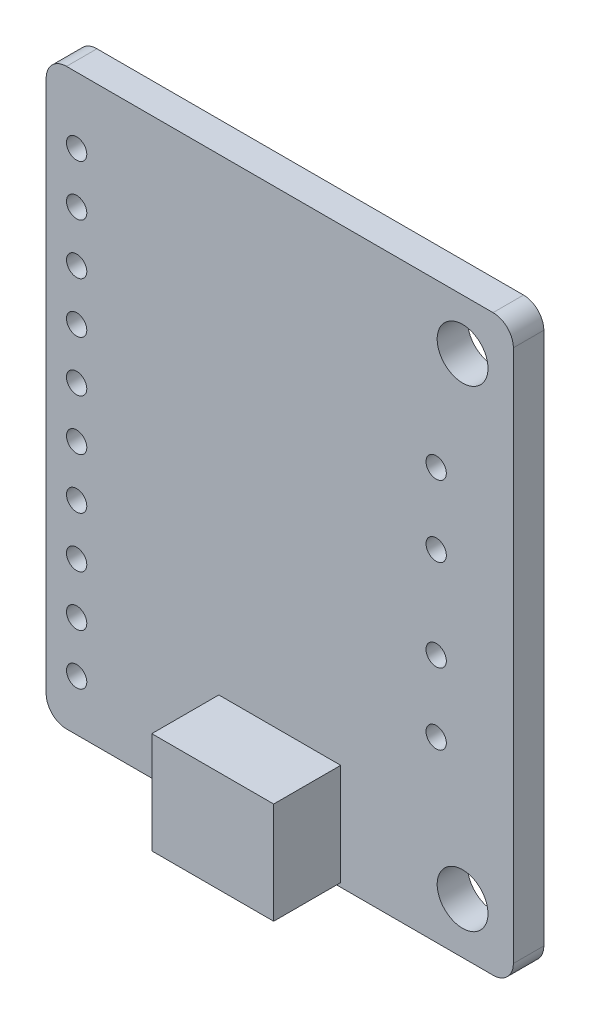
SolidWorks part; units mm, degrees
ref_plane "Front Plane" through (0, 0, 0) normal (0, 0, 1) x (1, 0, 0)
ref_plane "Top Plane" through (0, 0, 0) normal (0, 1, 0) x (1, 0, 0)
ref_plane "Right Plane" through (0, 0, 0) normal (1, 0, 0) x (0, 0, -1)
sketch "Sketch1" plane through (0, 0, 0) normal (0, 0, 1) x (1, 0, 0)
  line L1 (-10.5, -14.125) -> (10.5, -14.125)
  line L2 (-11.5, -13.125) -> (-11.5, 13.125)
  line L3 (-10.5, 14.125) -> (10.5, 14.125)
  line L4 (11.5, -13.125) -> (11.5, 13.125)
  line L5 (-11.5, -14.125) -> (11.5, 14.125) construction
  line L6 (-11.5, 14.125) -> (11.5, -14.125) construction
  arc A0 (-10.5, -14.125) -> (-11.5, -13.125) centre (-10.5, -13.125) cw
  arc A1 (10.5, -14.125) -> (11.5, -13.125) centre (10.5, -13.125) ccw
  arc A2 (10.5, 14.125) -> (11.5, 13.125) centre (10.5, 13.125) cw
  arc A3 (-11.5, 13.125) -> (-10.5, 14.125) centre (-10.5, 13.125) cw
  point P0 (0, 0)
  dimension "D3" = 1
  dimension "D1" = 28.25
  dimension "D2" = 23
extrude "Boss-Extrude1" add sketch "Sketch1" along normal blind 1.5
sketch "Sketch2" plane through (0, 0, 1.5) normal (0, 0, 1) x (1, 0, 0)
  line L0 (11.5, -13.125) -> (11.5, 13.125) construction
  line L1 (10.5, 14.125) -> (-10.5, 14.125) construction
  circle A0 centre (9, 11.625) radius 1.25
  dimension "D1" = 2.5
  dimension "D2" = 2.5
  dimension "D3" = 2.5
extrude "Cut-Extrude1" cut sketch "Sketch2" against normal through all
mirror "Mirror1" about plane through (0, 0, 0) normal (0, 1, 0) of "Cut-Extrude1"
sketch "Sketch3" plane through (0, 0, 1.5) normal (0, 0, 1) x (1, 0, 0)
  line L0 (-10.5, -14.125) -> (10.5, -14.125) construction
  line L1 (-11.5, 13.125) -> (-11.5, -13.125) construction
  circle A0 centre (-10, -11.625) radius 0.5
  dimension "D1" = 1
  dimension "D2" = 2.5
  dimension "D3" = 1.5
extrude "Cut-Extrude2" cut sketch "Sketch3" against normal through all
pattern_linear "LPattern1" count 10 spacing 2.5 along (0, 1, 0) of "Cut-Extrude2"
sketch "Sketch4" plane through (0, 0, 1.5) normal (0, 0, 1) x (1, 0, 0)
  line L0 (0, -0.825) -> (0, 0.825) construction
  line L1 (-3, -8.925) -> (3, -8.925)
  line L2 (-3, -8.925) -> (-3, -13.925)
  line L3 (-3, -13.925) -> (3, -13.925)
  line L4 (3, -8.925) -> (3, -13.925)
  line L5 (-3, -8.925) -> (3, -13.925) construction
  line L6 (-3, -13.925) -> (3, -8.925) construction
  line L7 (-10.5, -14.125) -> (10.5, -14.125) construction
  point P0 (0, -11.425)
  dimension "D1" = 6
  dimension "D2" = 5
  dimension "D3" = 0.2
extrude "Gain Switch" add sketch "Sketch4" along normal blind 3.3
sketch "Sketch5" plane through (0, 0, 1.5) normal (0, 0, 1) x (1, 0, 0)
  line L0 (11.5, -13.125) -> (11.5, 13.125) construction
  line L1 (10.5, 14.125) -> (-10.5, 14.125) construction
  circle A0 centre (7.7, 6.125) radius 0.5
  dimension "D1" = 1
  dimension "D2" = 3.8
  dimension "D3" = 8
extrude "Cut-Extrude3" cut sketch "Sketch5" against normal through all
pattern_linear "LPattern2" count 2 spacing 3.5 along (0, -1, 0) count 2 spacing 8 along (0, -1, 0) of "Cut-Extrude3"
